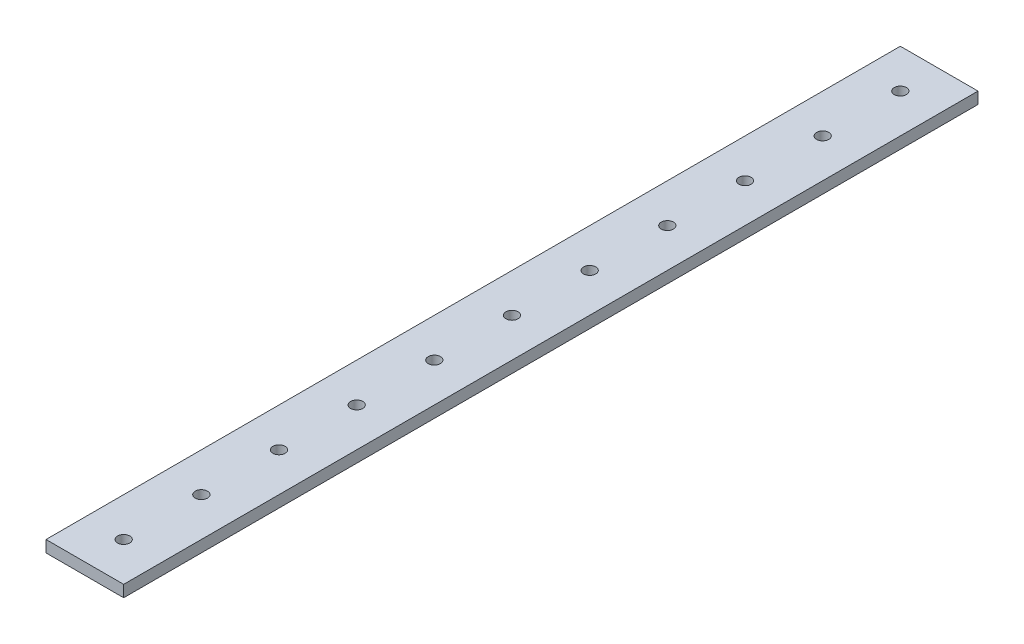
SolidWorks part; units mm, degrees
ref_plane "前视基准面" through (0, 0, 0) normal (0, 0, 1) x (1, 0, 0)
ref_plane "上视基准面" through (0, 0, 0) normal (0, 1, 0) x (1, 0, 0)
ref_plane "右视基准面" through (0, 0, 0) normal (1, 0, 0) x (0, 0, -1)
other "Configuration Table"
sketch "草图1" plane through (0, 0, 0) normal (0, 0, 1) x (1, 0, 0)
  line L1 (0, 0) -> (20, 0)
  line L2 (0, 0) -> (0, -3)
  line L3 (0, -3) -> (20, -3)
  line L4 (20, 0) -> (20, -3)
  dimension "D1" = 20
  dimension "D2" = 3
extrude "凸台-拉伸1" add sketch "草图1" along normal blind 220
sketch "草图2" plane through (0, 0, 0) normal (0, 1, 0) x (1, 0, 0)
  line L1 (20, 0) -> (0, 0) construction
  line L2 (10, 0) -> (10, -10) construction
  circle A0 centre (10, -10) radius 1.575
  circle A1 centre (10, -30) radius 1.575
  circle A2 centre (10, -50) radius 1.575
  circle A3 centre (10, -70) radius 1.575
  circle A4 centre (10, -90) radius 1.575
  circle A5 centre (10, -110) radius 1.575
  circle A6 centre (10, -130) radius 1.575
  circle A7 centre (10, -150) radius 1.575
  circle A8 centre (10, -170) radius 1.575
  circle A9 centre (10, -190) radius 1.575
  circle A10 centre (10, -210) radius 1.575
  circle A11 centre (10, -230) radius 1.575
  circle A12 centre (10, -250) radius 1.575
  circle A13 centre (10, -270) radius 1.575
  circle A14 centre (10, -290) radius 1.575
  circle A15 centre (10, -310) radius 1.575
  circle A16 centre (10, -330) radius 1.575
  circle A17 centre (10, -350) radius 1.575
  circle A18 centre (10, -370) radius 1.575
  circle A19 centre (10, -390) radius 1.575
  circle A20 centre (10, -410) radius 1.575
  circle A21 centre (10, -430) radius 1.575
  circle A22 centre (10, -450) radius 1.575
  circle A23 centre (10, -470) radius 1.575
  circle A24 centre (10, -490) radius 1.575
  circle A25 centre (10, -510) radius 1.575
  circle A26 centre (10, -530) radius 1.575
  circle A27 centre (10, -550) radius 1.575
  circle A28 centre (10, -570) radius 1.575
  circle A29 centre (10, -590) radius 1.575
  circle A30 centre (10, -610) radius 1.575
  circle A31 centre (10, -630) radius 1.575
  circle A32 centre (10, -650) radius 1.575
  dimension "D1" = 3.15
  dimension "D2" = 33
  dimension "D3" = 10
  dimension "D4" = 20
extrude "切除-拉伸1" cut sketch "草图2" against normal through all
